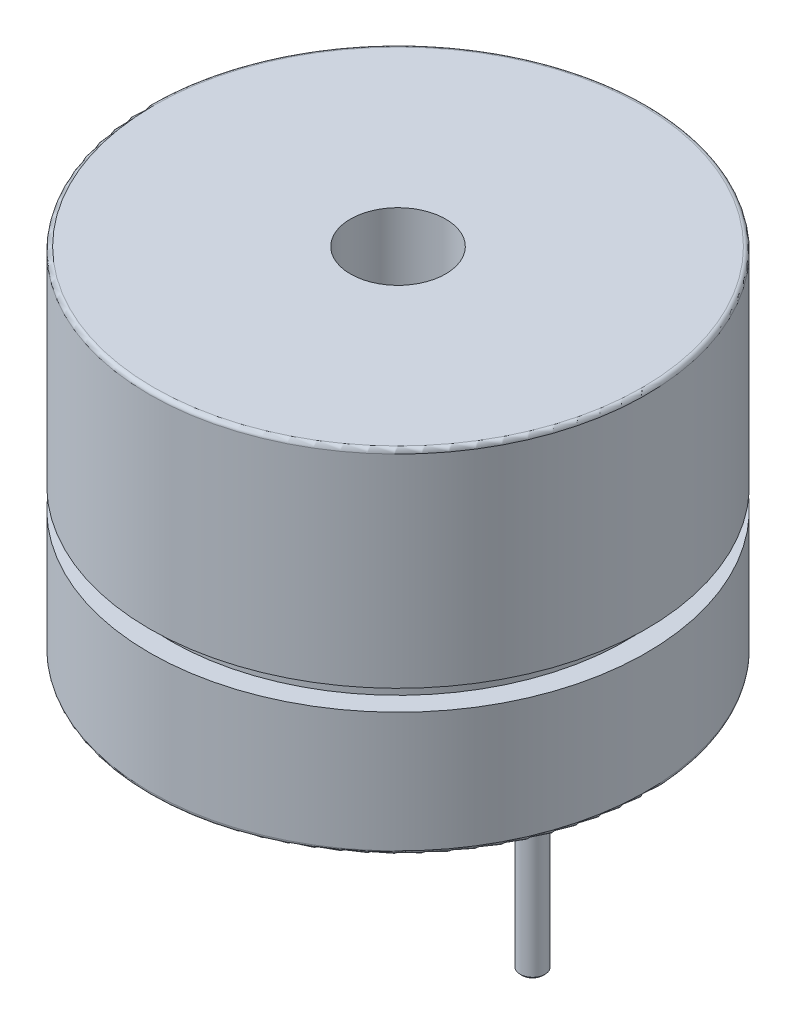
SolidWorks part; units mm, degrees
ref_plane "Front Plane" through (0, 0, 0) normal (0, 0, 1) x (1, 0, 0)
ref_plane "Top Plane" through (0, 0, 0) normal (0, 1, 0) x (1, 0, 0)
ref_plane "Right Plane" through (0, 0, 0) normal (1, 0, 0) x (0, 0, -1)
sketch "Sketch1" plane through (0, 0, 0) normal (0, 1, 0) x (1, 0, 0)
  circle A0 centre (0, 0) radius 6
  dimension "D1" = 12
extrude "Boss-Extrude1" add sketch "Sketch1" along normal blind 3
sketch "Sketch2" plane through (0, 3, 0) normal (0, 1, 0) x (1, 0, 0)
  circle A0 centre (0, 0) radius 5.5
  circle A1 centre (0, 0) radius 6
  circle A2 centre (0, 0) radius 6
  dimension "D1" = 0
  dimension "D2" = 0.5
extrude "Boss-Extrude2" add sketch "Sketch2" along normal blind 0.5 contours A0
sketch "Sketch3" plane through (0, 3.5, 0) normal (0, 1, 0) x (1, 0, 0)
  circle A0 centre (0, 0) radius 6 construction
  circle A1 centre (0, 0) radius 6
extrude "Boss-Extrude3" add sketch "Sketch3" along normal blind 5
sketch "Sketch4" plane through (0, 8.5, 0) normal (0, 1, 0) x (1, 0, 0)
  circle A0 centre (0, 0) radius 1.15
  dimension "D1" = 2.3
extrude "Cut-Extrude1" cut sketch "Sketch4" against normal blind 5
sketch "Sketch5" plane through (0, 0, 0) normal (0, -1, 0) x (1, 0, 0)
  line L0 (-6, 0) -> (6, 0) construction
  line L1 (0, 6) -> (0, -6) construction
  circle A0 centre (0, 0) radius 6 construction
  circle A1 centre (-3.25, 0) radius 0.3
  circle A2 centre (3.25, 0) radius 0.3
  dimension "D1" = 0.6
  dimension "D2" = 6.5
extrude "Boss-Extrude4" add sketch "Sketch5" along normal blind 5
fillet "Fillet1" radius 0.1 2 edges at (0, 0, 6) (0, 8.5, 6)
chamfer "Chamfer1" distance 0.05 angle 45 2 edges at (3.25, -5, 0.3) (-3.25, -5, -0.3)
